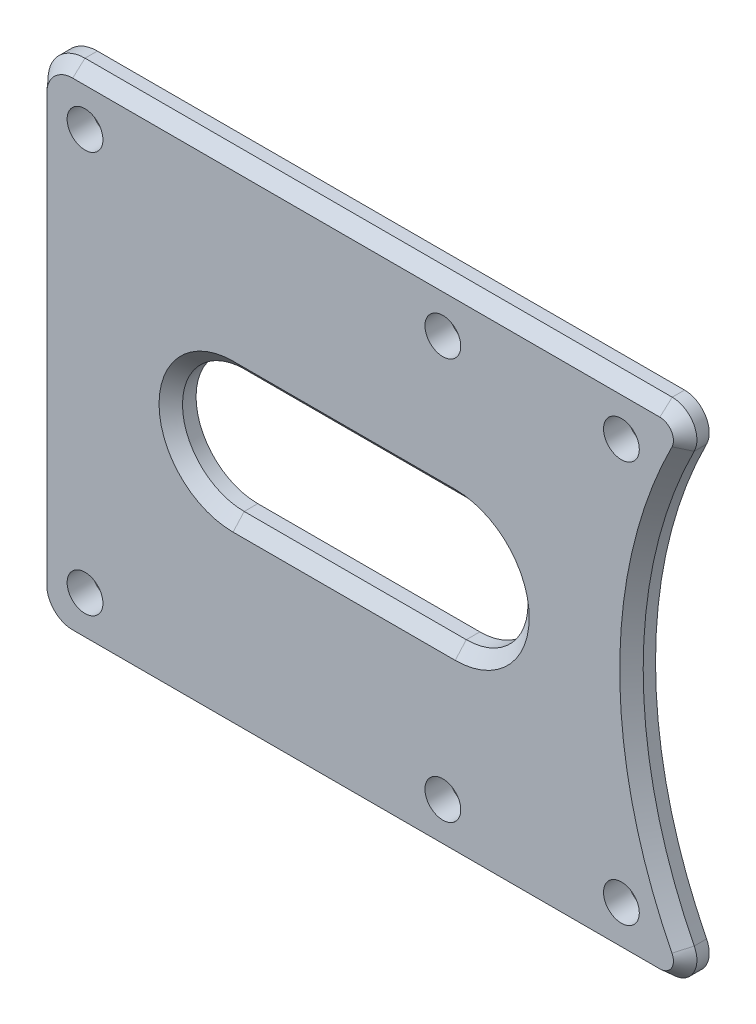
SolidWorks part; units mm, degrees
material "Hexcel AS4C (3000 丝)"
ref_plane "前视基准面" through (0, 0, 0) normal (0, 0, 1) x (1, 0, 0)
ref_plane "上视基准面" through (0, 0, 0) normal (0, 1, 0) x (1, 0, 0)
ref_plane "右视基准面" through (0, 0, 0) normal (1, 0, 0) x (0, 0, -1)
sketch "草图2" plane through (0, 0, 0) normal (0, 0, 1) x (1, 0, 0)
  line L0 (148.2649, -17.264) -> (148.2649, 17.264)
  line L1 (151.2649, -20.264) -> (198.852, -20.264)
  line L2 (151.2649, 20.264) -> (198.852, 20.264)
  line L3 (164.2649, 0) -> (182.2649, 0) construction
  line L4 (164.2649, 5) -> (182.2649, 5)
  line L5 (164.2649, -5) -> (182.2649, -5)
  arc A0 (151.2649, -20.264) -> (148.2649, -17.264) centre (151.2649, -17.264) cw
  arc A1 (148.2649, 17.264) -> (151.2649, 20.264) centre (151.2649, 17.264) cw
  arc A2 (200.6371, -17.3621) -> (200.6371, 17.3621) centre (235, 0) cw
  circle A3 centre (235, 0) radius 9 construction
  arc A4 (200.6371, 17.3621) -> (198.852, 20.264) centre (198.852, 18.264) ccw
  arc A5 (198.852, -20.264) -> (200.6371, -17.3621) centre (198.852, -18.264) ccw
  circle A6 centre (152.2649, 16.264) radius 1.45
  circle A7 centre (181.2649, 16.264) radius 1.45
  circle A8 centre (195.7351, 16.264) radius 1.45
  circle A9 centre (152.2649, -16.264) radius 1.45
  circle A10 centre (181.2649, -16.264) radius 1.45
  circle A11 centre (195.7351, -16.264) radius 1.45
  circle A12 centre (181.2649, -16.264) radius 1.5 construction
  arc A13 (164.2649, 5) -> (164.2649, -5) centre (164.2649, 0) ccw
  arc A14 (182.2649, -5) -> (182.2649, 5) centre (182.2649, 0) ccw
  point P39 (173.2649, 0)
  dimension "D1" = 38.5
  dimension "D2" = 2
  dimension "D3" = 2.9
  dimension "D6" = 16
  dimension "D4" = 10
  dimension "D5" = 18
extrude "凸台-拉伸1" add sketch "草图2" along normal blind 2
chamfer "倒角2" distance 1 angle 42 8 edges at (175.0585, 20.264, 2) (149.1436, 19.3854, 2) (200.5555, 19.3119, 2) (148.2649, 0, 2) (196.5, 0, 2) (149.1436, -19.3854, 2) (200.5555, -19.3119, 2) (175.0585, -20.264, 2)
chamfer "倒角3" distance 1 angle 42 4 edges at (173.2649, 5, 2) (159.2649, 0, 2) (187.2649, 0, 2) (173.2649, -5, 2)
